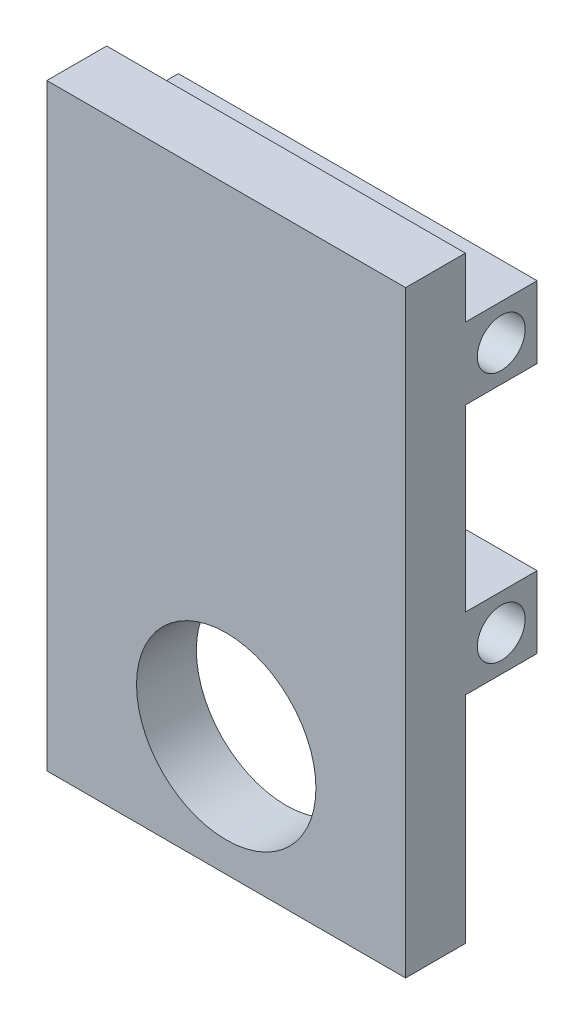
SolidWorks part; units mm, degrees
ref_plane "前视基准面" through (0, 0, 0) normal (0, 0, 1) x (1, 0, 0)
ref_plane "上视基准面" through (0, 0, 0) normal (0, 1, 0) x (1, 0, 0)
ref_plane "右视基准面" through (0, 0, 0) normal (1, 0, 0) x (0, 0, -1)
other "Configuration Table"
sketch "草图1" plane through (0, 0, 0) normal (1, 0, 0) x (0, 0, -1)
  line L0 (5, -2) -> (5, 28)
  line L1 (5, -50) -> (-5, -50)
  line L2 (5, -50) -> (5, -14)
  line L3 (5, 50) -> (-5, 50)
  line L4 (-5, -50) -> (-5, 50)
  line L5 (5, -50) -> (-5, 50) construction
  line L6 (5, 50) -> (-5, -50) construction
  line L7 (-2.3044, 34) -> (34.7302, 34) construction
  line L8 (5, 40) -> (5, 50)
  line L9 (17, 28) -> (5, 28)
  line L10 (17, 28) -> (17, 40)
  line L11 (17, 40) -> (5, 40)
  line L13 (17, 28) -> (5, 40) construction
  line L14 (17, 40) -> (5, 28) construction
  line L15 (-1.1689, -8) -> (34.7343, -8) construction
  line L16 (17, -14) -> (5, -14)
  line L17 (17, -14) -> (17, -2)
  line L18 (17, -2) -> (5, -2)
  line L20 (17, -14) -> (5, -2) construction
  line L21 (17, -2) -> (5, -14) construction
  circle A0 centre (11, 34) radius 4
  circle A1 centre (11, -8) radius 4
  point P0 (0, 0)
  point P6 (11, -8)
  point P10 (11, 34)
  dimension "D9" = 8
  dimension "D10" = 8
  dimension "D1" = 12
  dimension "D2" = 12
  dimension "D3" = 12
  dimension "D4" = 100
  dimension "D5" = 10
  dimension "D6" = 12
  dimension "D7" = 42
  dimension "D8" = 10
extrude "凸台-拉伸1" add sketch "草图1" along normal blind 60
sketch "草图2" plane through (0, 0, 5) normal (0, 0, 1) x (1, 0, 0)
  line L0 (30, 50) -> (30, -50) construction
  line L1 (60, 50) -> (0, 50) construction
  line L2 (60, -50) -> (0, -50) construction
  circle A0 centre (30, -30) radius 15
  dimension "D2" = 30
  dimension "D1" = 20
extrude "切除-拉伸1" cut sketch "草图2" against normal blind 60
